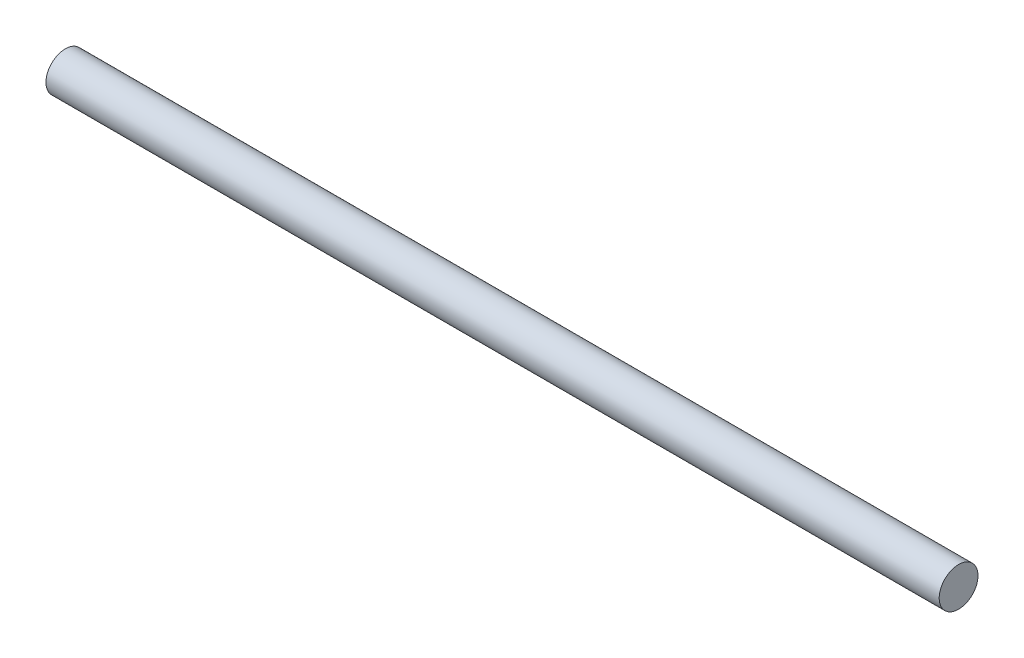
SolidWorks part; units mm, degrees
material "Copper"
ref_plane "Front Plane" through (0, 0, 0) normal (0, 0, 1) x (1, 0, 0)
ref_plane "Top Plane" through (0, 0, 0) normal (0, 1, 0) x (1, 0, 0)
ref_plane "Right Plane" through (0, 0, 0) normal (1, 0, 0) x (0, 0, -1)
sketch "Sketch1" plane through (0, 0, 0) normal (1, 0, 0) x (0, 0, -1)
  circle A0 centre (0, 0) radius 0.2921
  dimension "D1" = 0.5842
extrude "Boss-Extrude1" add sketch "Sketch1" along normal blind 13.45
